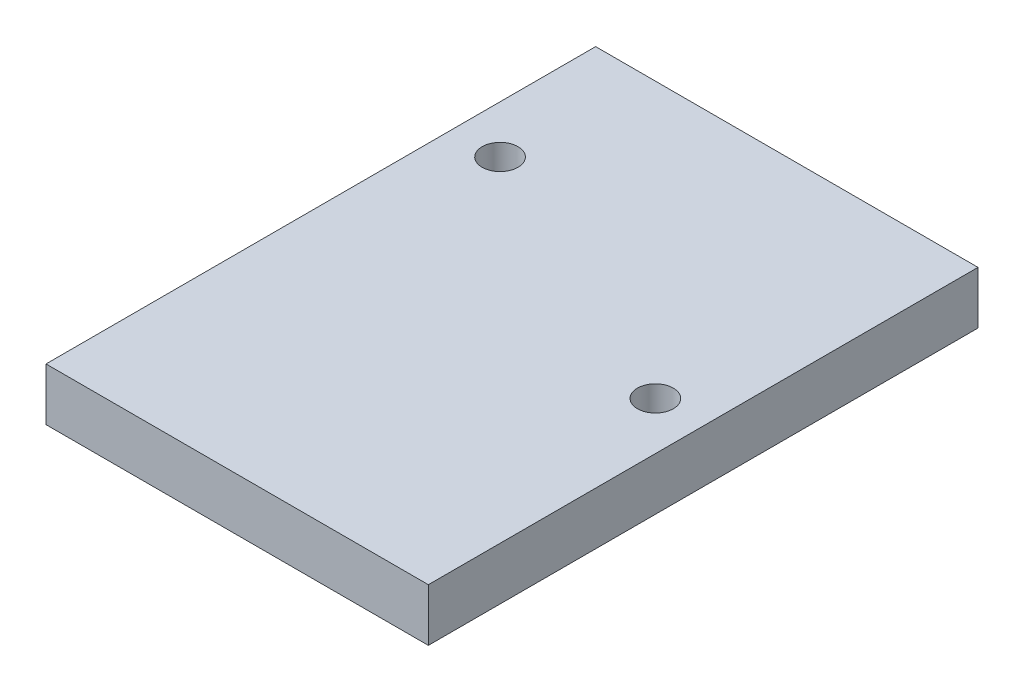
SolidWorks part; units mm, degrees
ref_plane "前视基准面" through (0, 0, 0) normal (0, 0, 1) x (1, 0, 0)
ref_plane "上视基准面" through (0, 0, 0) normal (0, 1, 0) x (1, 0, 0)
ref_plane "右视基准面" through (0, 0, 0) normal (1, 0, 0) x (0, 0, -1)
other "Configuration Table"
sketch "草图1" plane through (0, 0, 0) normal (0, 1, 0) x (1, 0, 0)
  line L1 (0, 0) -> (16, 0)
  line L2 (0, 0) -> (0, -23)
  line L3 (0, -23) -> (16, -23)
  line L4 (16, 0) -> (16, -23)
  circle A3 centre (14, -11.5) radius 0.75
  circle A5 centre (2, -6) radius 0.75
  dimension "D3" = 11.5
  dimension "D6" = 6
  dimension "D7" = 1.5
  dimension "D1" = 23
  dimension "D2" = 16
  dimension "D4" = 2
  dimension "D5" = 2
extrude "凸台-拉伸1" add sketch "草图1" along normal blind 2.2
